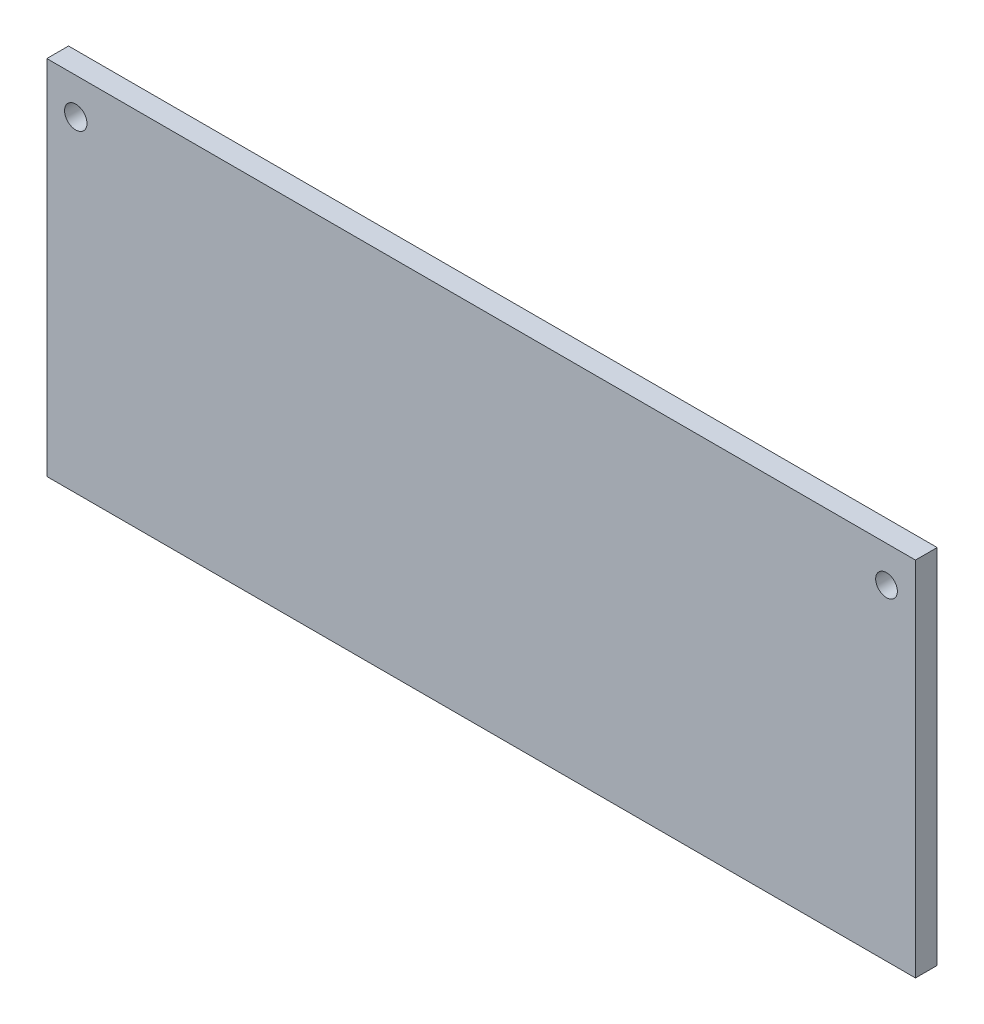
SolidWorks part; units mm, degrees
ref_plane "前视基准面" through (0, 0, 0) normal (0, 0, 1) x (1, 0, 0)
ref_plane "上视基准面" through (0, 0, 0) normal (0, 1, 0) x (1, 0, 0)
ref_plane "右视基准面" through (0, 0, 0) normal (1, 0, 0) x (0, 0, -1)
other "Configuration Table"
sketch "草图1" plane through (0, 0, 0) normal (0, 0, 1) x (1, 0, 0)
  line L1 (60, -25) -> (-60, -25)
  line L2 (60, -25) -> (60, 25)
  line L3 (60, 25) -> (-60, 25)
  line L4 (-60, -25) -> (-60, 25)
  line L5 (60, -25) -> (-60, 25) construction
  line L6 (60, 25) -> (-60, -25) construction
  point P0 (0, 0)
  dimension "D1" = 120
  dimension "D2" = 50
extrude "凸台-拉伸1" add sketch "草图1" along normal blind 3
sketch "草图3" plane through (0, 0, 0) normal (0, 0, -1) x (-1, 0, 0)
  line L2 (60, 25) -> (60, -25) construction
  line L3 (-60, 25) -> (60, 25) construction
  line L5 (-60, -25) -> (-60, 25) construction
  circle A0 centre (-56, 20) radius 1.5
  circle A1 centre (56, 20) radius 1.55
  point P10 (80.5695, 9.4417)
  point P15 (-78.4713, 21.9258)
  dimension "D1" = 4
  dimension "D2" = 5
  dimension "D3" = 4
  dimension "D4" = 5
extrude "切除-拉伸2" cut sketch "草图3" against normal blind 10
